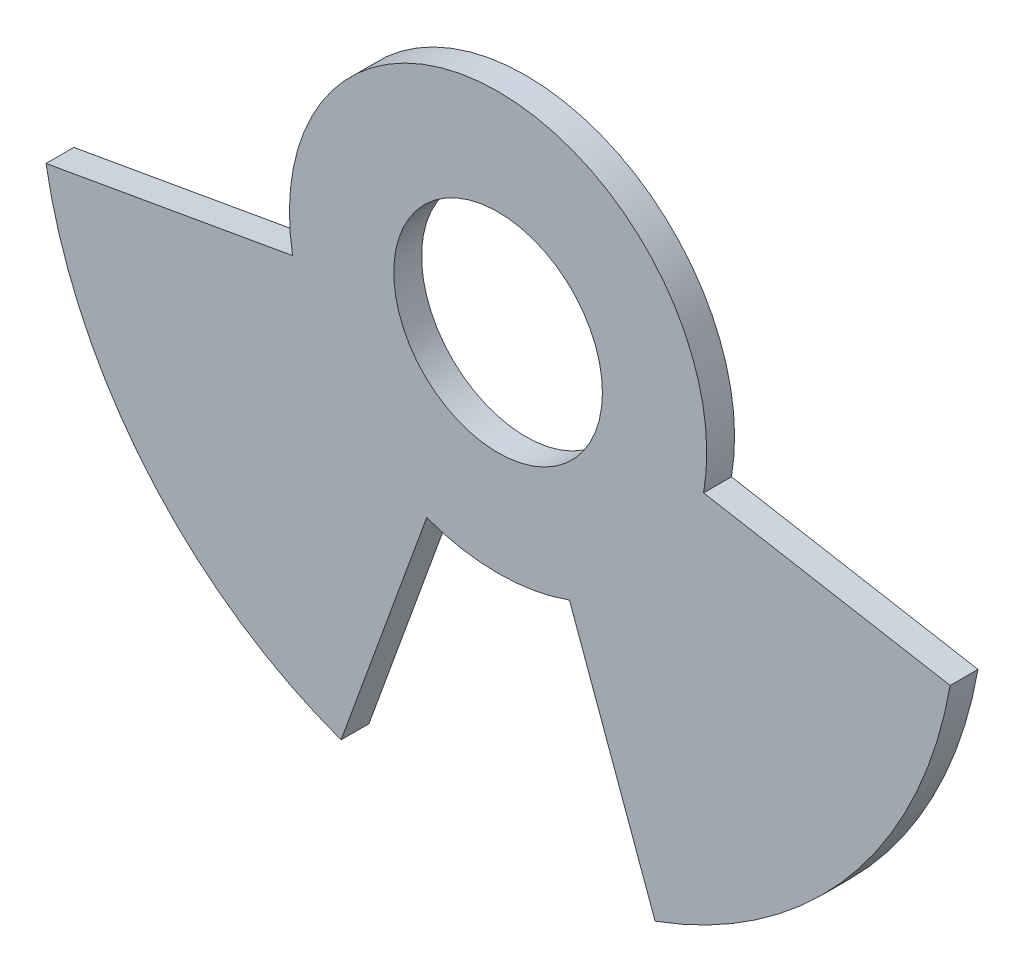
SolidWorks part; units mm, degrees
material "Malleable Cast Iron"
ref_plane "Front Plane" through (0, 0, 0) normal (0, 0, 1) x (1, 0, 0)
ref_plane "Top Plane" through (0, 0, 0) normal (0, 1, 0) x (1, 0, 0)
ref_plane "Right Plane" through (0, 0, 0) normal (1, 0, 0) x (0, 0, -1)
sketch "Sketch1" plane through (0, 0, 0) normal (0, 0, 1) x (1, 0, 0)
  line L0 (0, 0) -> (0, 3.3) construction
  line L1 (-0.513, -1.4095) -> (-1.1287, -3.101)
  line L2 (-1.4772, -0.2605) -> (-3.2499, -0.573)
  line L3 (0.513, -1.4095) -> (1.1287, -3.101)
  line L4 (1.4772, -0.2605) -> (3.2499, -0.573)
  circle A0 centre (0, 0) radius 0.75 construction
  circle A1 centre (0, 0) radius 1.5 construction
  circle A2 centre (0, 0) radius 3.3 construction
  circle A3 centre (0, 0) radius 0.75
  arc A4 (1.4772, -0.2605) -> (-1.4772, -0.2605) centre (0, 0) ccw
  arc A5 (-1.1287, -3.101) -> (-3.2499, -0.573) centre (0, 0) cw
  arc A6 (0.513, -1.4095) -> (-0.513, -1.4095) centre (0, 0) cw
  arc A7 (1.1287, -3.101) -> (3.2499, -0.573) centre (0, 0) ccw
  dimension "D1" = 1.5
  dimension "D2" = 3
  dimension "D3" = 6.6
  dimension "D4" = 20
  dimension "D5" = 80
extrude "Boss-Extrude1" add sketch "Sketch1" along normal blind 0.2
